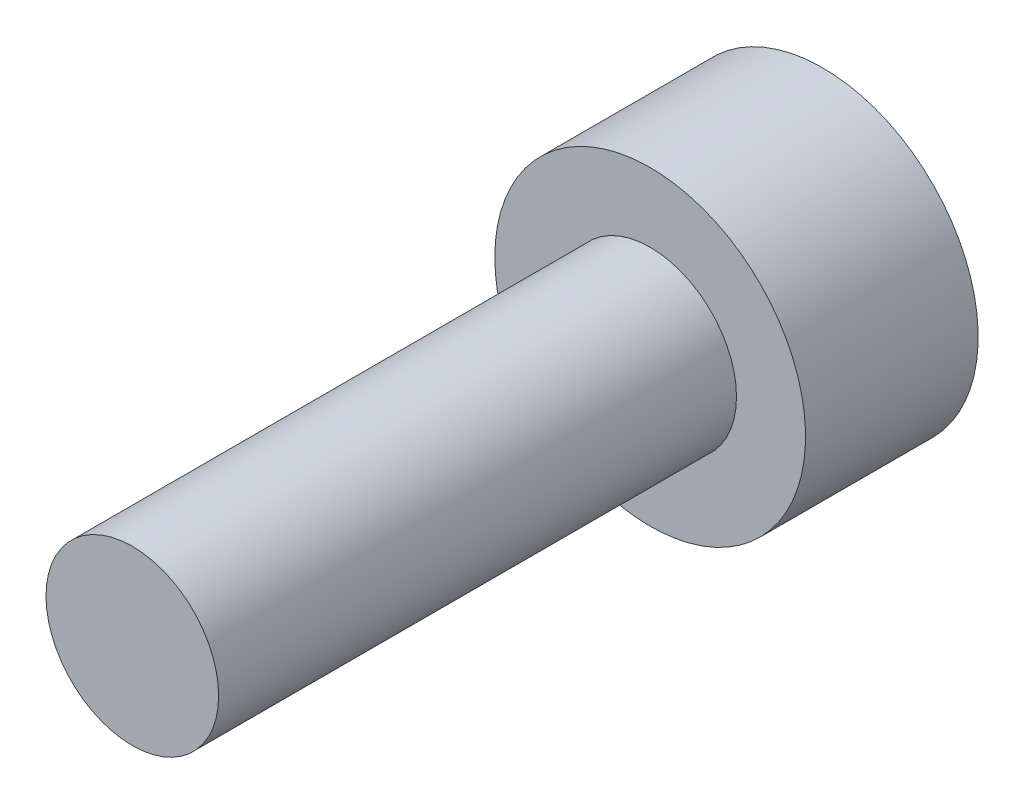
SolidWorks part; units mm, degrees
ref_plane "前视基准面" through (0, 0, 0) normal (0, 0, 1) x (1, 0, 0)
ref_plane "上视基准面" through (0, 0, 0) normal (0, 1, 0) x (1, 0, 0)
ref_plane "右视基准面" through (0, 0, 0) normal (1, 0, 0) x (0, 0, -1)
sketch "草图1" plane through (0, 0, 0) normal (0, 0, 1) x (1, 0, 0)
  circle A0 centre (0, 0) radius 2.5
  dimension "D1" = 5
extrude "凸台-拉伸1" add sketch "草图1" along normal blind 15
sketch "草图2" plane through (0, 0, 0) normal (0, 0, -1) x (-1, 0, 0)
  circle A0 centre (0, 0) radius 4.5
  dimension "D1" = 9
extrude "凸台-拉伸2" add sketch "草图2" along normal blind 5 contours A0
sketch "草图3" plane through (0, 0, -5) normal (0, 0, -1) x (-1, 0, 0)
  line L1 (0, 2.8868) -> (-2.5, 1.4434)
  line L2 (-2.5, 1.4434) -> (-2.5, -1.4434)
  line L3 (-2.5, -1.4434) -> (0, -2.8868)
  line L4 (0, -2.8868) -> (2.5, -1.4434)
  line L5 (2.5, -1.4434) -> (2.5, 1.4434)
  line L6 (2.5, 1.4434) -> (0, 2.8868)
  circle A0 centre (0, 0) radius 2.5 construction
  dimension "D1" = 5
extrude "切除-拉伸1" cut sketch "草图3" against normal blind 2.9
